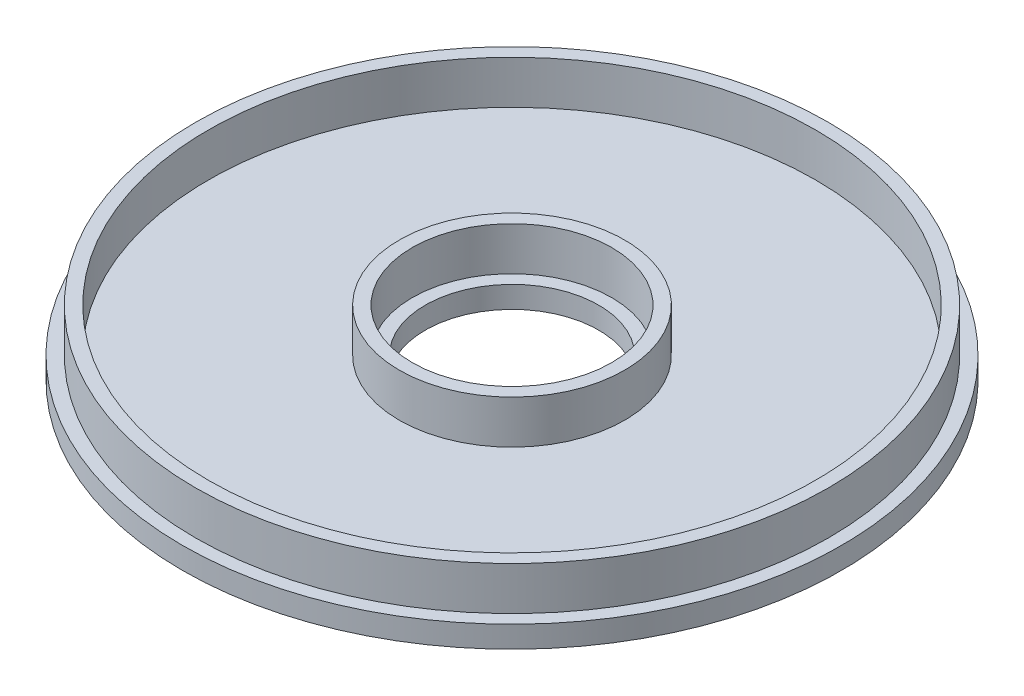
SolidWorks part; units mm, degrees
ref_plane "Front Plane" through (0, 0, 0) normal (0, 0, 1) x (1, 0, 0)
ref_plane "Top Plane" through (0, 0, 0) normal (0, 1, 0) x (1, 0, 0)
ref_plane "Right Plane" through (0, 0, 0) normal (1, 0, 0) x (0, 0, -1)
sketch "Sketch1" plane through (0, 0, 0) normal (0, 1, 0) x (1, 0, 0)
  circle A0 centre (0, 0) radius 20
  circle A1 centre (0, 0) radius 76
  dimension "D1" = 152
  dimension "D2" = 40
extrude "Boss-Extrude1" add sketch "Sketch1" along normal blind 5
sketch "Sketch2" plane through (0, 5, 0) normal (0, 1, 0) x (1, 0, 0)
  circle A0 centre (0, 0) radius 23
  circle A1 centre (0, 0) radius 26
  circle A3 centre (0, 0) radius 70
  circle A4 centre (0, 0) radius 73
  circle A5 centre (0, 0) radius 73
  dimension "D2" = 46
  dimension "D1" = 3
  dimension "D3" = 3
  dimension "D4" = 3
extrude "Boss-Extrude2" add sketch "Sketch2" along normal blind 10 contours A5 A3 | A1 A0
